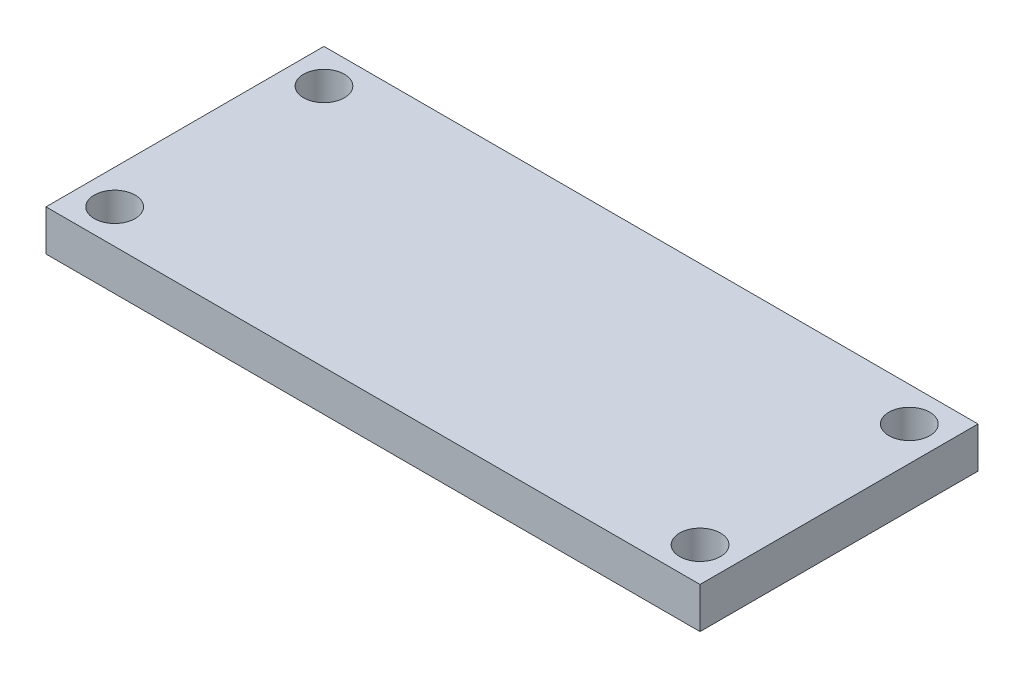
SolidWorks part; units mm, degrees
ref_plane "Front Plane" through (0, 0, 0) normal (0, 0, 1) x (1, 0, 0)
ref_plane "Top Plane" through (0, 0, 0) normal (0, 1, 0) x (1, 0, 0)
ref_plane "Right Plane" through (0, 0, 0) normal (1, 0, 0) x (0, 0, -1)
sketch "Sketch1" plane through (0, 0, 0) normal (0, 1, 0) x (1, 0, 0)
  line L0 (-20, 4.3) -> (-15.8, 4.3)
  line L1 (-20, -8.5) -> (20, -8.5)
  line L2 (-20, -8.5) -> (-20, 8.5)
  line L3 (-20, 8.5) -> (20, 8.5)
  line L4 (20, -8.5) -> (20, 8.5)
  line L5 (-20, -8.5) -> (20, 8.5) construction
  line L6 (-20, 8.5) -> (20, -8.5) construction
  line L7 (-15.8, 4.3) -> (-15.8, 8.5)
  line L8 (-20, 8.5) -> (-15.8, 4.3) construction
  line L9 (0, 0) -> (32.0486, 0) construction
  line L10 (0, 0) -> (0, 18.2841) construction
  line L11 (-15.8, 4.3) -> (-20, 4.3)
  line L12 (-15.8, 8.5) -> (-15.8, 4.3)
  line L13 (-20, 4.3) -> (-15.8, 4.3)
  line L14 (-15.8, 4.3) -> (-15.8, 8.5)
  line L15 (-15.8, 4.3) -> (-20, 4.3)
  line L16 (-15.8, 8.5) -> (-15.8, 4.3)
  line L17 (-20, 4.3) -> (-15.8, 4.3)
  line L18 (-15.8, 4.3) -> (-15.8, 8.5)
  line L19 (-15.8, 4.3) -> (-20, 4.3)
  line L20 (-15.8, 8.5) -> (-15.8, 4.3)
  line L21 (-20, 4.3) -> (-15.8, 4.3)
  line L22 (-15.8, 4.3) -> (-15.8, 8.5)
  line L23 (-15.8, 4.3) -> (-20, 4.3)
  line L24 (-15.8, 8.5) -> (-15.8, 4.3)
  line L25 (-20, -4.3) -> (-15.8, -4.3)
  line L26 (-15.8, -4.3) -> (-15.8, -8.5)
  line L27 (20, 4.3) -> (15.8, 4.3)
  line L28 (15.8, 4.3) -> (15.8, 8.5)
  line L29 (20, -4.3) -> (15.8, -4.3)
  line L30 (15.8, -4.3) -> (15.8, -8.5)
  line L31 (-15.8, 4.3) -> (-15.8, -4.3)
  line L32 (15.8, 4.3) -> (15.8, -4.3)
  circle A0 centre (-17.9, 6.4) radius 1.25
  circle A1 centre (-17.9, -6.4) radius 1.25
  circle A2 centre (17.9, 6.4) radius 1.25
  circle A3 centre (17.9, -6.4) radius 1.25
  point P0 (0, 0)
  point P28 (0, 0)
  dimension "D3" = 2.5
  dimension "D1" = 40
  dimension "D2" = 17
  dimension "D4" = 4.2
extrude "Boss-Extrude1" add sketch "Sketch1" along normal blind 2.5 contours L32 L28 L3 L7 L31 L26 L1 L30 | L31 L0 L2 L25 | L26 L25 L2 L1 A1 | L28 L27 L4 L3 A2 | L27 L32 L29 L4 | L29 L30 L1 L4 A3 | L0 L7 L3 L2 A0
